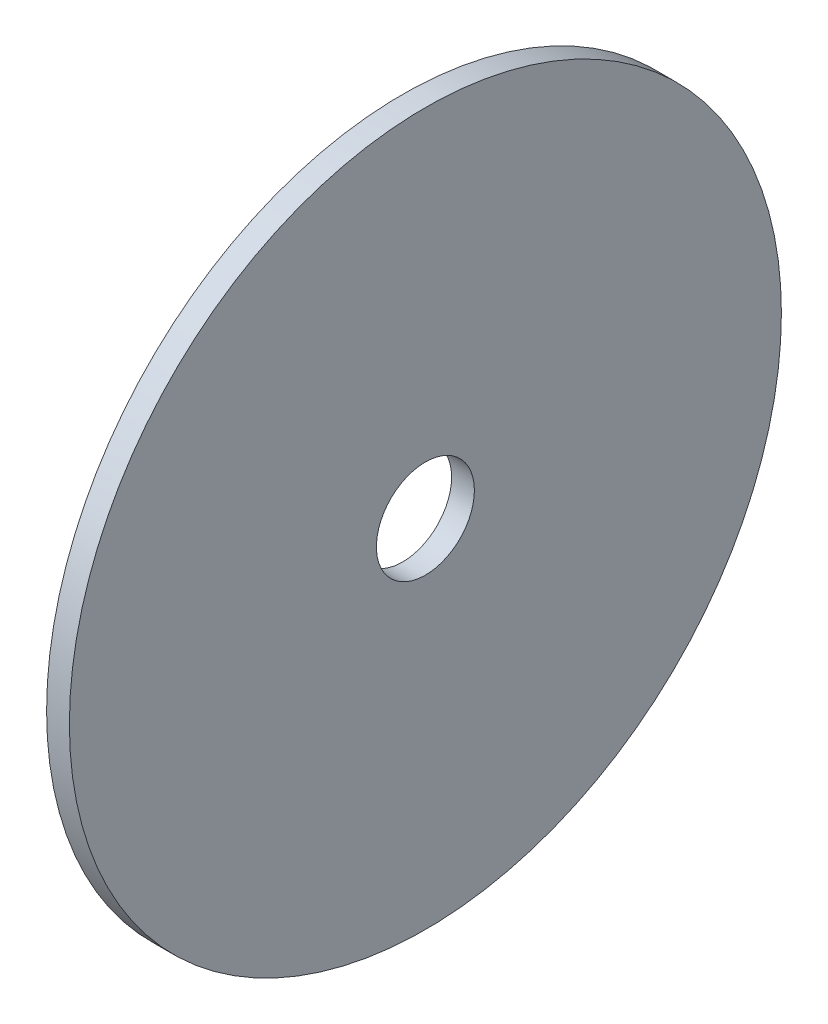
SolidWorks part; units mm, degrees
material "Cast Stainless Steel"
ref_plane "Front Plane" through (0, 0, 0) normal (0, 0, 1) x (1, 0, 0)
ref_plane "Top Plane" through (0, 0, 0) normal (0, 1, 0) x (1, 0, 0)
ref_plane "Right Plane" through (0, 0, 0) normal (1, 0, 0) x (0, 0, -1)
sketch "Sketch1" plane through (0, 0, 0) normal (1, 0, 0) x (0, 0, -1)
  circle A0 centre (0, 0) radius 31.75
  circle A1 centre (0, 0) radius 4.3688
  dimension "OD" = 63.5
  dimension "ID" = 8.7376
extrude "Boss-Extrude1" add sketch "Sketch1" along normal blind 2.032
